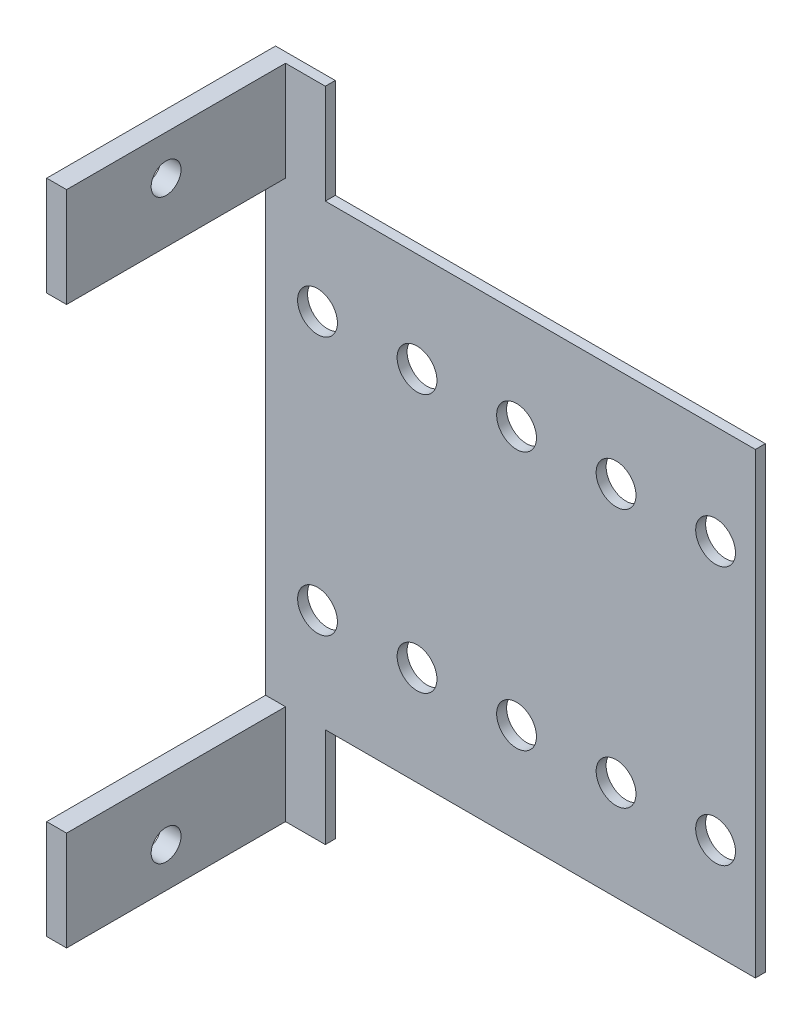
SolidWorks part; units mm, degrees
ref_plane "Plan de face" through (0, 0, 0) normal (0, 0, 1) x (1, 0, 0)
ref_plane "Plan de dessus" through (0, 0, 0) normal (0, 1, 0) x (1, 0, 0)
ref_plane "Plan de droite" through (0, 0, 0) normal (1, 0, 0) x (0, 0, -1)
sketch "Esquisse1" plane through (0, 0, 0) normal (0, 0, 1) x (1, 0, 0)
  line L0 (0, 16.5) -> (30, 16.5) construction
  line L1 (3, 5) -> (24.6081, 5)
  line L2 (0, 0) -> (0, 33)
  line L3 (0, 33) -> (3, 33)
  line L4 (24.6081, 28) -> (24.6081, 5)
  line L5 (3, 33) -> (3, 28)
  line L6 (3, 28) -> (24.6081, 28)
  line L7 (3, 0) -> (3, 5)
  line L8 (0, 0) -> (3, 0)
  dimension "D1" = 33
  dimension "D2" = 5
  dimension "D3" = 3
extrude "Boss.-Extru.1" add sketch "Esquisse1" along normal blind 0.5
sketch "Esquisse2" plane through (0, 0, 0.5) normal (0, 0, 1) x (1, 0, 0)
  line L0 (0, 16.5) -> (24.6081, 16.5) construction
  line L1 (0, 33) -> (0, 0) construction
  line L2 (24.6081, 5) -> (24.6081, 28) construction
  line L3 (0, 0) -> (1, 0)
  line L4 (0, 33) -> (1, 33)
  line L5 (0, 33) -> (0, 28)
  line L6 (0, 28) -> (1, 28)
  line L7 (1, 33) -> (1, 28)
  line L8 (0, 0) -> (0, 5)
  line L9 (0, 5) -> (1, 5)
  line L10 (1, 0) -> (1, 5)
  circle A0 centre (22.6081, 16.5) radius 1
  circle A1 centre (17.6081, 16.5) radius 1
  circle A2 centre (12.6081, 16.5) radius 1
  circle A3 centre (7.6081, 16.5) radius 1
  circle A4 centre (2.6081, 16.5) radius 1
  line M1 (0, 0) -> (3, 0)
  line M7 (3, 33) -> (0, 33)
  line M8 (0, 33) -> (0, 0)
  dimension "D2" = 2
  dimension "D1" = 2
  dimension "D4" = 1
  dimension "D3" = 5
extrude "Boss.-Extru.2" add sketch "Esquisse2" along normal blind 11 contours L7 L6 M7 M8 | L10 L9 M1 M8
sketch "Esquisse3" plane through (0, 0, 0.5) normal (0, 0, 1) x (1, 0, 0)
sketch "Esquisse6" plane through (0, 0, 0.5) normal (0, 0, 1) x (1, 0, 0)
  line L0 (0, 10) -> (24.6081, 10) construction
  line L1 (0, 28) -> (0, 5) construction
  line L2 (24.6081, 5) -> (24.6081, 28) construction
  line L3 (3, 5) -> (24.6081, 5) construction
  line L4 (0, 16.5) -> (24.6081, 16.5) construction
  circle A0 centre (22.6081, 10) radius 1
  circle A1 centre (17.6081, 10) radius 1
  circle A2 centre (12.6081, 10) radius 1
  circle A3 centre (7.6081, 10) radius 1
  circle A4 centre (2.6081, 10) radius 1
  circle A5 centre (2.6081, 23) radius 1
  circle A6 centre (7.6081, 23) radius 1
  circle A7 centre (12.6081, 23) radius 1
  circle A8 centre (17.6081, 23) radius 1
  circle A9 centre (22.6081, 23) radius 1
  dimension "D2" = 2
  dimension "D1" = 5
  dimension "D3" = 2
  dimension "D4" = 5
extrude "Enlèv. mat.-Extru.3" cut sketch "Esquisse6" against normal blind 11
sketch "Esquisse7" plane through (0, 0, 0) normal (-1, 0, 0) x (0, 0, 1)
  line L1 (11.5, 28) -> (0.5, 28) construction
  line L3 (0, 16.5) -> (0.5, 16.5) construction
  line L4 (0, 33) -> (0, 0) construction
  line L5 (0.5, 28) -> (0.5, 5) construction
  circle A0 centre (6.5, 31) radius 0.75
  circle A1 centre (6.5, 2) radius 0.75
  dimension "D1" = 1.5
  dimension "D2" = 3
  dimension "D3" = 6
extrude "Enlèv. mat.-Extru.4" cut sketch "Esquisse7" against normal blind 11
